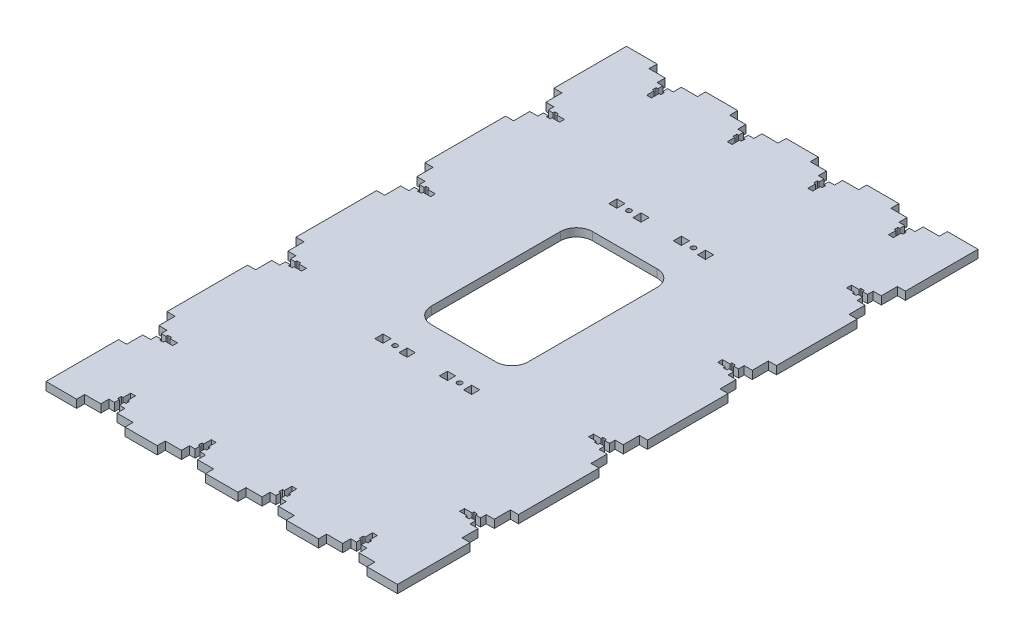
SolidWorks part; units mm, degrees
ref_plane "Front Plane" through (0, 0, 0) normal (0, 0, 1) x (1, 0, 0)
ref_plane "Top Plane" through (0, 0, 0) normal (0, 1, 0) x (1, 0, 0)
ref_plane "Right Plane" through (0, 0, 0) normal (1, 0, 0) x (0, 0, -1)
sketch "Sketch1" plane through (0, 0, 0) normal (0, 1, 0) x (1, 0, 0)
  line L0 (0, 0) -> (0, 175) construction
  line L13 (109, 180) -> (90, 180)
  line L14 (90, 180) -> (90, 175)
  line L15 (90, 175) -> (80, 175)
  line L16 (60, 175) -> (60, 180)
  line L17 (60, 180) -> (40, 180)
  line L18 (40, 180) -> (40, 175)
  line L19 (40, 175) -> (30, 175)
  line L20 (-10, 175) -> (-10, 180)
  line L21 (-10, 180) -> (10, 180)
  line L22 (10, 180) -> (10, 175)
  line L24 (-40, 175) -> (-40, 180)
  line L25 (-40, 180) -> (-60, 180)
  line L26 (-60, 180) -> (-60, 175)
  line L27 (-60, 175) -> (-70, 175)
  line L28 (-90, 175) -> (-90, 180)
  line L29 (-90, 180) -> (-109, 180)
  line L30 (109, 180) -> (109, 135)
  line L31 (109, 135) -> (104, 135)
  line L32 (104, 135) -> (104, 125)
  line L33 (104, 105) -> (109, 105)
  line L34 (109, 105) -> (109, 55)
  line L35 (109, 55) -> (104, 55)
  line L36 (104, 55) -> (104, 45)
  line L37 (104, 25) -> (109, 25)
  line L38 (109, 25) -> (109, -25)
  line L39 (109, -25) -> (104, -25)
  line L40 (104, -25) -> (104, -35)
  line L41 (104, -55) -> (109, -55)
  line L42 (109, -55) -> (109, -105)
  line L43 (109, -105) -> (104, -105)
  line L44 (104, -105) -> (104, -115)
  line L45 (104, -135) -> (109, -135)
  line L46 (109, -135) -> (109, -180)
  line L47 (-109, -135) -> (-109, -180)
  line L48 (-104, -135) -> (-109, -135)
  line L49 (-104, -105) -> (-104, -115)
  line L50 (-109, -105) -> (-104, -105)
  line L51 (-109, -55) -> (-109, -105)
  line L52 (-104, -55) -> (-109, -55)
  line L53 (-104, -25) -> (-104, -35)
  line L54 (-109, -25) -> (-104, -25)
  line L55 (-109, 25) -> (-109, -25)
  line L56 (-104, 25) -> (-109, 25)
  line L57 (-104, 55) -> (-104, 45)
  line L58 (-109, 55) -> (-104, 55)
  line L59 (-109, 105) -> (-109, 55)
  line L60 (-104, 105) -> (-109, 105)
  line L61 (-104, 135) -> (-104, 125)
  line L62 (-109, 135) -> (-104, 135)
  line L63 (-109, 180) -> (-109, 135)
  line L64 (0, 0) -> (119.1007, 0) construction
  line L65 (109, -180) -> (90, -180)
  line L66 (-90, -180) -> (-109, -180)
  line L67 (-90, -175) -> (-90, -180)
  line L68 (-60, -175) -> (-70, -175)
  line L69 (-60, -180) -> (-60, -175)
  line L70 (-40, -180) -> (-60, -180)
  line L71 (-40, -175) -> (-40, -180)
  line L72 (-10, -175) -> (-20, -175)
  line L73 (10, -180) -> (10, -175)
  line L74 (-10, -180) -> (10, -180)
  line L75 (-10, -175) -> (-10, -180)
  line L76 (40, -175) -> (30, -175)
  line L77 (40, -180) -> (40, -175)
  line L78 (60, -180) -> (40, -180)
  line L79 (60, -175) -> (60, -180)
  line L80 (90, -175) -> (80, -175)
  line L81 (90, -180) -> (90, -175)
  line L82 (-10, 95.05) -> (-10, 90)
  line L83 (-20, 70) -> (20, 70)
  line L84 (-30, 60) -> (-30, -20)
  line L85 (-20, -30) -> (20, -30)
  line L86 (30, 60) -> (30, -20)
  line L87 (-30, 70) -> (30, -30) construction
  line L88 (-30, -30) -> (30, 70) construction
  line L89 (30, 95.05) -> (25, 95.05)
  line L90 (30, 95.05) -> (30, 90)
  line L91 (30, 90) -> (25, 90)
  line L92 (10, 95.05) -> (10, 90)
  line L93 (-10, 175) -> (-20, 175)
  line L94 (-93.7, 41.5) -> (-93.7, 42.6)
  line L95 (-30, 90) -> (-25, 90)
  line L96 (-99, 41.5) -> (-99, 45)
  line L97 (-93.7, 121.5) -> (-93.7, 122.6)
  line L98 (-30, 95.05) -> (-25, 95.05)
  line L99 (-30, 95.05) -> (-30, 90)
  line L100 (56.5463, 20) -> (-43.4482, 20) construction
  line L109 (15, 95.05) -> (15, 90)
  line L110 (25, 95.05) -> (25, 90)
  line L111 (15, 95.05) -> (10, 95.05)
  line L112 (-96, 41.5) -> (-99, 41.5)
  line L113 (-99, 121.5) -> (-99, 125)
  line L114 (15, 90) -> (10, 90)
  line L115 (-15, 95.05) -> (-15, 90)
  line L116 (-25, 95.05) -> (-25, 90)
  line L117 (-15, 95.05) -> (-10, 95.05)
  line L118 (-93.7, 37.4) -> (-93.7, 38.5)
  line L119 (-96, 121.5) -> (-99, 121.5)
  line L120 (-15, 90) -> (-10, 90)
  line L121 (-93.7, 42.6) -> (-96, 42.6)
  line L122 (-96, 38.5) -> (-96, 37.4)
  line L123 (-89, 41.5) -> (-93.7, 41.5)
  line L124 (-89, 38.5) -> (-89, 41.5)
  line L125 (-93.7, 38.5) -> (-89, 38.5)
  line L126 (-96, 42.6) -> (-96, 41.5)
  line L127 (-96, 37.4) -> (-93.7, 37.4)
  line L128 (-99, 38.5) -> (-96, 38.5)
  line L129 (-15, -50) -> (-10, -50)
  line L130 (-15, -55.05) -> (-10, -55.05)
  line L131 (-25, -55.05) -> (-25, -50)
  line L132 (-15, -55.05) -> (-15, -50)
  line L133 (15, -50) -> (10, -50)
  line L134 (15, -55.05) -> (10, -55.05)
  line L135 (25, -55.05) -> (25, -50)
  line L136 (15, -55.05) -> (15, -50)
  line L137 (-30, -55.05) -> (-30, -50)
  line L138 (-30, -55.05) -> (-25, -55.05)
  line L139 (-30, -50) -> (-25, -50)
  line L140 (10, -55.05) -> (10, -50)
  line L141 (30, -50) -> (25, -50)
  line L142 (30, -55.05) -> (30, -50)
  line L143 (30, -55.05) -> (25, -55.05)
  line L144 (-10, -55.05) -> (-10, -50)
  line L145 (-99, 45) -> (-104, 45)
  line L146 (-93.7, 117.4) -> (-93.7, 118.5)
  line L147 (-104, 35) -> (-99, 35)
  line L148 (-99, 38.5) -> (-99, 35)
  line L149 (-93.7, 122.6) -> (-96, 122.6)
  line L150 (99, 38.5) -> (99, 35)
  line L151 (-96, 118.5) -> (-96, 117.4)
  line L152 (-89, 121.5) -> (-93.7, 121.5)
  line L153 (-89, 118.5) -> (-89, 121.5)
  line L154 (-93.7, 118.5) -> (-89, 118.5)
  line L155 (-96, 122.6) -> (-96, 121.5)
  line L156 (-96, 117.4) -> (-93.7, 117.4)
  line L157 (-99, 118.5) -> (-96, 118.5)
  line L158 (-99, 125) -> (-104, 125)
  line L159 (-104, 115) -> (-99, 115)
  line L160 (-99, 118.5) -> (-99, 115)
  line L161 (-73.5, 164.7) -> (-72.4, 164.7)
  line L162 (-73.5, 170) -> (-70, 170)
  line L163 (-73.5, 167) -> (-73.5, 170)
  line L164 (-77.6, 164.7) -> (-76.5, 164.7)
  line L165 (-72.4, 164.7) -> (-72.4, 167)
  line L166 (-76.5, 167) -> (-77.6, 167)
  line L167 (-73.5, 160) -> (-73.5, 164.7)
  line L168 (-76.5, 160) -> (-73.5, 160)
  line L169 (-76.5, 164.7) -> (-76.5, 160)
  line L170 (-72.4, 167) -> (-73.5, 167)
  line L171 (-77.6, 167) -> (-77.6, 164.7)
  line L172 (-76.5, 170) -> (-76.5, 167)
  line L173 (-70, 170) -> (-70, 175)
  line L174 (-80, 175) -> (-80, 170)
  line L175 (-76.5, 170) -> (-80, 170)
  line L176 (-23.5, 164.7) -> (-22.4, 164.7)
  line L177 (-23.5, 170) -> (-20, 170)
  line L178 (-23.5, 167) -> (-23.5, 170)
  line L179 (-27.6, 164.7) -> (-26.5, 164.7)
  line L180 (-22.4, 164.7) -> (-22.4, 167)
  line L181 (-26.5, 167) -> (-27.6, 167)
  line L182 (-23.5, 160) -> (-23.5, 164.7)
  line L183 (-26.5, 160) -> (-23.5, 160)
  line L184 (-26.5, 164.7) -> (-26.5, 160)
  line L185 (-22.4, 167) -> (-23.5, 167)
  line L186 (-27.6, 167) -> (-27.6, 164.7)
  line L187 (-26.5, 170) -> (-26.5, 167)
  line L188 (-20, 170) -> (-20, 175)
  line L189 (-30, 175) -> (-30, 170)
  line L190 (-26.5, 170) -> (-30, 170)
  line L191 (104, 35) -> (99, 35)
  line L192 (99, 45) -> (104, 45)
  line L193 (99, 38.5) -> (96, 38.5)
  line L194 (96, 37.4) -> (93.7, 37.4)
  line L195 (96, 42.6) -> (96, 41.5)
  line L196 (93.7, 38.5) -> (89, 38.5)
  line L197 (89, 38.5) -> (89, 41.5)
  line L198 (89, 41.5) -> (93.7, 41.5)
  line L199 (96, 38.5) -> (96, 37.4)
  line L200 (93.7, 42.6) -> (96, 42.6)
  line L201 (93.7, 37.4) -> (93.7, 38.5)
  line L202 (96, 41.5) -> (99, 41.5)
  line L203 (99, 41.5) -> (99, 45)
  line L204 (93.7, 41.5) -> (93.7, 42.6)
  line L205 (26.5, 170) -> (30, 170)
  line L206 (30, 175) -> (30, 170)
  line L207 (20, 170) -> (20, 175)
  line L208 (26.5, 170) -> (26.5, 167)
  line L209 (27.6, 167) -> (27.6, 164.7)
  line L210 (22.4, 167) -> (23.5, 167)
  line L211 (26.5, 164.7) -> (26.5, 160)
  line L212 (26.5, 160) -> (23.5, 160)
  line L213 (23.5, 160) -> (23.5, 164.7)
  line L214 (26.5, 167) -> (27.6, 167)
  line L215 (22.4, 164.7) -> (22.4, 167)
  line L216 (27.6, 164.7) -> (26.5, 164.7)
  line L217 (23.5, 167) -> (23.5, 170)
  line L218 (23.5, 170) -> (20, 170)
  line L219 (23.5, 164.7) -> (22.4, 164.7)
  line L220 (76.5, 170) -> (80, 170)
  line L221 (80, 175) -> (80, 170)
  line L222 (70, 170) -> (70, 175)
  line L223 (76.5, 170) -> (76.5, 167)
  line L224 (77.6, 167) -> (77.6, 164.7)
  line L225 (72.4, 167) -> (73.5, 167)
  line L226 (76.5, 164.7) -> (76.5, 160)
  line L227 (76.5, 160) -> (73.5, 160)
  line L228 (73.5, 160) -> (73.5, 164.7)
  line L229 (76.5, 167) -> (77.6, 167)
  line L230 (72.4, 164.7) -> (72.4, 167)
  line L231 (77.6, 164.7) -> (76.5, 164.7)
  line L232 (73.5, 167) -> (73.5, 170)
  line L233 (73.5, 170) -> (70, 170)
  line L234 (73.5, 164.7) -> (72.4, 164.7)
  line L235 (99, 118.5) -> (99, 115)
  line L236 (104, 115) -> (99, 115)
  line L237 (99, 125) -> (104, 125)
  line L238 (99, 118.5) -> (96, 118.5)
  line L239 (96, 117.4) -> (93.7, 117.4)
  line L240 (96, 122.6) -> (96, 121.5)
  line L241 (93.7, 118.5) -> (89, 118.5)
  line L242 (89, 118.5) -> (89, 121.5)
  line L243 (89, 121.5) -> (93.7, 121.5)
  line L244 (96, 118.5) -> (96, 117.4)
  line L245 (93.7, 122.6) -> (96, 122.6)
  line L246 (93.7, 117.4) -> (93.7, 118.5)
  line L247 (96, 121.5) -> (99, 121.5)
  line L248 (99, 121.5) -> (99, 125)
  line L249 (93.7, 121.5) -> (93.7, 122.6)
  line L250 (93.7, -41.5) -> (93.7, -42.6)
  line L251 (99, -41.5) -> (99, -45)
  line L252 (96, -41.5) -> (99, -41.5)
  line L253 (93.7, -37.4) -> (93.7, -38.5)
  line L254 (93.7, -42.6) -> (96, -42.6)
  line L255 (96, -38.5) -> (96, -37.4)
  line L256 (89, -41.5) -> (93.7, -41.5)
  line L257 (89, -38.5) -> (89, -41.5)
  line L258 (93.7, -38.5) -> (89, -38.5)
  line L259 (96, -42.6) -> (96, -41.5)
  line L260 (96, -37.4) -> (93.7, -37.4)
  line L261 (99, -38.5) -> (96, -38.5)
  line L262 (99, -45) -> (104, -45)
  line L263 (104, -35) -> (99, -35)
  line L264 (99, -38.5) -> (99, -35)
  line L265 (104, -55) -> (104, -45)
  line L266 (93.7, -121.5) -> (93.7, -122.6)
  line L267 (99, -121.5) -> (99, -125)
  line L268 (96, -121.5) -> (99, -121.5)
  line L269 (93.7, -117.4) -> (93.7, -118.5)
  line L270 (93.7, -122.6) -> (96, -122.6)
  line L271 (96, -118.5) -> (96, -117.4)
  line L272 (89, -121.5) -> (93.7, -121.5)
  line L273 (89, -118.5) -> (89, -121.5)
  line L274 (93.7, -118.5) -> (89, -118.5)
  line L275 (96, -122.6) -> (96, -121.5)
  line L276 (96, -117.4) -> (93.7, -117.4)
  line L277 (99, -118.5) -> (96, -118.5)
  line L278 (99, -125) -> (104, -125)
  line L279 (104, -115) -> (99, -115)
  line L280 (99, -118.5) -> (99, -115)
  line L281 (104, -135) -> (104, -125)
  line L282 (73.5, -164.7) -> (72.4, -164.7)
  line L283 (73.5, -170) -> (70, -170)
  line L284 (73.5, -167) -> (73.5, -170)
  line L285 (77.6, -164.7) -> (76.5, -164.7)
  line L286 (72.4, -164.7) -> (72.4, -167)
  line L287 (76.5, -167) -> (77.6, -167)
  line L288 (73.5, -160) -> (73.5, -164.7)
  line L289 (76.5, -160) -> (73.5, -160)
  line L290 (76.5, -164.7) -> (76.5, -160)
  line L291 (72.4, -167) -> (73.5, -167)
  line L292 (77.6, -167) -> (77.6, -164.7)
  line L293 (76.5, -170) -> (76.5, -167)
  line L294 (70, -170) -> (70, -175)
  line L295 (80, -175) -> (80, -170)
  line L296 (76.5, -170) -> (80, -170)
  line L297 (23.5, -164.7) -> (22.4, -164.7)
  line L298 (23.5, -170) -> (20, -170)
  line L299 (23.5, -167) -> (23.5, -170)
  line L300 (27.6, -164.7) -> (26.5, -164.7)
  line L301 (22.4, -164.7) -> (22.4, -167)
  line L302 (26.5, -167) -> (27.6, -167)
  line L303 (23.5, -160) -> (23.5, -164.7)
  line L304 (26.5, -160) -> (23.5, -160)
  line L305 (26.5, -164.7) -> (26.5, -160)
  line L306 (22.4, -167) -> (23.5, -167)
  line L307 (27.6, -167) -> (27.6, -164.7)
  line L308 (26.5, -170) -> (26.5, -167)
  line L309 (20, -170) -> (20, -175)
  line L310 (30, -175) -> (30, -170)
  line L311 (26.5, -170) -> (30, -170)
  line L312 (-26.5, -170) -> (-30, -170)
  line L313 (-30, -175) -> (-30, -170)
  line L314 (-20, -170) -> (-20, -175)
  line L315 (-26.5, -170) -> (-26.5, -167)
  line L316 (-27.6, -167) -> (-27.6, -164.7)
  line L317 (-22.4, -167) -> (-23.5, -167)
  line L318 (-26.5, -164.7) -> (-26.5, -160)
  line L319 (-26.5, -160) -> (-23.5, -160)
  line L320 (-23.5, -160) -> (-23.5, -164.7)
  line L321 (-26.5, -167) -> (-27.6, -167)
  line L322 (-22.4, -164.7) -> (-22.4, -167)
  line L323 (-27.6, -164.7) -> (-26.5, -164.7)
  line L324 (-23.5, -167) -> (-23.5, -170)
  line L325 (-23.5, -170) -> (-20, -170)
  line L326 (-23.5, -164.7) -> (-22.4, -164.7)
  line L327 (-76.5, -170) -> (-80, -170)
  line L328 (-80, -175) -> (-80, -170)
  line L329 (-70, -170) -> (-70, -175)
  line L330 (-76.5, -170) -> (-76.5, -167)
  line L331 (-77.6, -167) -> (-77.6, -164.7)
  line L332 (-72.4, -167) -> (-73.5, -167)
  line L333 (-76.5, -164.7) -> (-76.5, -160)
  line L334 (-76.5, -160) -> (-73.5, -160)
  line L335 (-73.5, -160) -> (-73.5, -164.7)
  line L336 (-76.5, -167) -> (-77.6, -167)
  line L337 (-72.4, -164.7) -> (-72.4, -167)
  line L338 (-77.6, -164.7) -> (-76.5, -164.7)
  line L339 (-73.5, -167) -> (-73.5, -170)
  line L340 (-73.5, -170) -> (-70, -170)
  line L341 (-73.5, -164.7) -> (-72.4, -164.7)
  line L342 (-99, -118.5) -> (-99, -115)
  line L343 (-104, -115) -> (-99, -115)
  line L344 (-99, -125) -> (-104, -125)
  line L345 (-99, -118.5) -> (-96, -118.5)
  line L346 (-96, -117.4) -> (-93.7, -117.4)
  line L347 (-96, -122.6) -> (-96, -121.5)
  line L348 (-93.7, -118.5) -> (-89, -118.5)
  line L349 (-89, -118.5) -> (-89, -121.5)
  line L350 (-89, -121.5) -> (-93.7, -121.5)
  line L351 (-96, -118.5) -> (-96, -117.4)
  line L352 (-93.7, -122.6) -> (-96, -122.6)
  line L353 (-93.7, -117.4) -> (-93.7, -118.5)
  line L354 (-96, -121.5) -> (-99, -121.5)
  line L355 (-99, -121.5) -> (-99, -125)
  line L356 (-93.7, -121.5) -> (-93.7, -122.6)
  line L357 (-99, -38.5) -> (-99, -35)
  line L358 (-104, -35) -> (-99, -35)
  line L359 (-99, -45) -> (-104, -45)
  line L360 (-99, -38.5) -> (-96, -38.5)
  line L361 (-96, -37.4) -> (-93.7, -37.4)
  line L362 (-96, -42.6) -> (-96, -41.5)
  line L363 (-93.7, -38.5) -> (-89, -38.5)
  line L364 (-89, -38.5) -> (-89, -41.5)
  line L365 (-89, -41.5) -> (-93.7, -41.5)
  line L366 (-96, -38.5) -> (-96, -37.4)
  line L367 (-93.7, -42.6) -> (-96, -42.6)
  line L368 (-93.7, -37.4) -> (-93.7, -38.5)
  line L369 (-96, -41.5) -> (-99, -41.5)
  line L370 (-99, -41.5) -> (-99, -45)
  line L371 (-93.7, -41.5) -> (-93.7, -42.6)
  line L372 (70, -175) -> (60, -175)
  line L373 (20, -175) -> (10, -175)
  line L374 (-80, -175) -> (-90, -175)
  line L375 (-30, -175) -> (-40, -175)
  line L376 (-104, -125) -> (-104, -135)
  line L377 (-104, -45) -> (-104, -55)
  line L378 (-104, 35) -> (-104, 25)
  line L379 (-104, 115) -> (-104, 105)
  line L380 (-80, 175) -> (-90, 175)
  line L381 (-30, 175) -> (-40, 175)
  line L382 (20, 175) -> (10, 175)
  line L383 (70, 175) -> (60, 175)
  line L384 (104, 115) -> (104, 105)
  line L385 (104, -45) -> (104, -55)
  line L386 (104, -35) -> (104, -25)
  line L387 (104, 35) -> (104, 25)
  line L388 (104, -125) -> (104, -135)
  line L389 (104, -115) -> (104, -105)
  arc A0 (20, 70) -> (30, 60) centre (20, 60) cw
  arc A1 (-30, 60) -> (-20, 70) centre (-20, 60) cw
  arc A2 (-20, -30) -> (-30, -20) centre (-20, -20) cw
  arc A3 (20, -30) -> (30, -20) centre (20, -20) ccw
  circle A4 centre (20, 92.525) radius 1.5
  circle A6 centre (-20, 92.525) radius 1.5
  circle A7 centre (-20, -52.525) radius 1.5
  circle A8 centre (20, -52.525) radius 1.5
  point P13 (0, 0)
  point P37 (0, 20)
  point P89 (20, 92.525)
  point P389 (0, 0)
  point P390 (0, 0)
  point P391 (0, 0)
  point P392 (0, 0)
  point P393 (0, 0)
  dimension "D11" = 10
  dimension "D12" = 10
  dimension "D13" = 10
  dimension "D14" = 10
  dimension "D21" = 5
  dimension "D23" = 10
  dimension "D24" = 3
  dimension "D1" = 30
  dimension "D2" = 5
  dimension "D3" = 360
  dimension "D4" = 218
  dimension "D5" = 30
  dimension "D6" = 20
  dimension "D7" = 50
  dimension "D8" = 20
  dimension "D9" = 100
  dimension "D10" = 60
  dimension "D15" = 5.05
  dimension "D16" = 20
  dimension "D17" = 10
  dimension "D18" = 20
  dimension "D19" = 5
  dimension "D20" = 5
  dimension "D22" = 5
  dimension "D25" = 10
  dimension "D28" = 10
  dimension "D29" = 10
extrude "Boss-Extrude1" add sketch "Sketch1" along normal blind 5 contours L387 L191 L150 L193 L199 L194 L201 L196 L197 L198 L204 L200 L195 L202 L203 L192 L36 L35 L34 L33 L384 L236 L235 L238 L244 L239 L246 L241 L242 L243 L249 L245 L240 L247 L248 L237 L32 L31 L30 L13 L14 L15 L221 L220 L223 L229 L224 L231 L226 L227 L228
